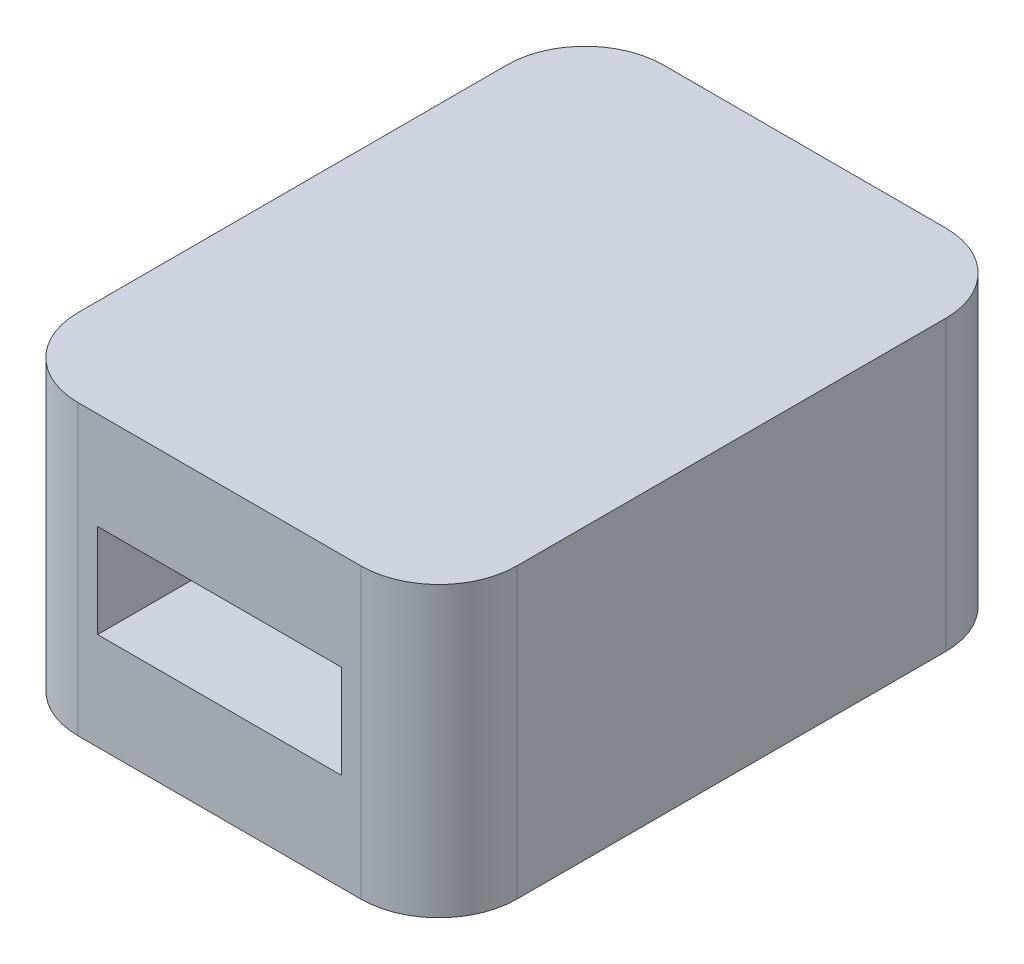
SolidWorks part; units mm, degrees
ref_plane "Front Plane" through (0, 0, 0) normal (0, 0, 1) x (1, 0, 0)
ref_plane "Top Plane" through (0, 0, 0) normal (0, 1, 0) x (1, 0, 0)
ref_plane "Right Plane" through (0, 0, 0) normal (1, 0, 0) x (0, 0, -1)
sketch "Profile Sketch" plane through (0, 0, 0) normal (0, 0, 1) x (1, 0, 0)
  line L0 (0, 1.2) -> (0, 3.7) construction
  line L1 (-3.125, -1.2) -> (3.125, -1.2)
  line L2 (-3.125, -1.2) -> (-3.125, 1.2)
  line L3 (-3.125, 1.2) -> (3.125, 1.2)
  line L4 (3.125, -1.2) -> (3.125, 1.2)
  line L5 (-3.125, -1.2) -> (3.125, 1.2) construction
  line L6 (-3.125, 1.2) -> (3.125, -1.2) construction
  line L7 (-5.625, -3.7) -> (5.625, -3.7)
  line L8 (-5.625, -3.7) -> (-5.625, 3.7)
  line L9 (-5.625, 3.7) -> (5.625, 3.7)
  line L10 (5.625, -3.7) -> (5.625, 3.7)
  line L11 (-5.625, -3.7) -> (5.625, 3.7) construction
  line L12 (-5.625, 3.7) -> (5.625, -3.7) construction
  line L13 (-3.125, 0) -> (-5.625, 0) construction
  point P0 (0, 0)
  point P6 (0, 0)
  dimension "D1" = 6.25
  dimension "D2" = 2.5
  dimension "D3" = 2.4
extrude "Profile Extrude" add sketch "Profile Sketch" along normal blind 15
fillet "Corner Fillets" radius 2 4 edges at (-5.625, 0, 0) (5.625, 0, 0) (5.625, 0, 15) (-5.625, 0, 15)
